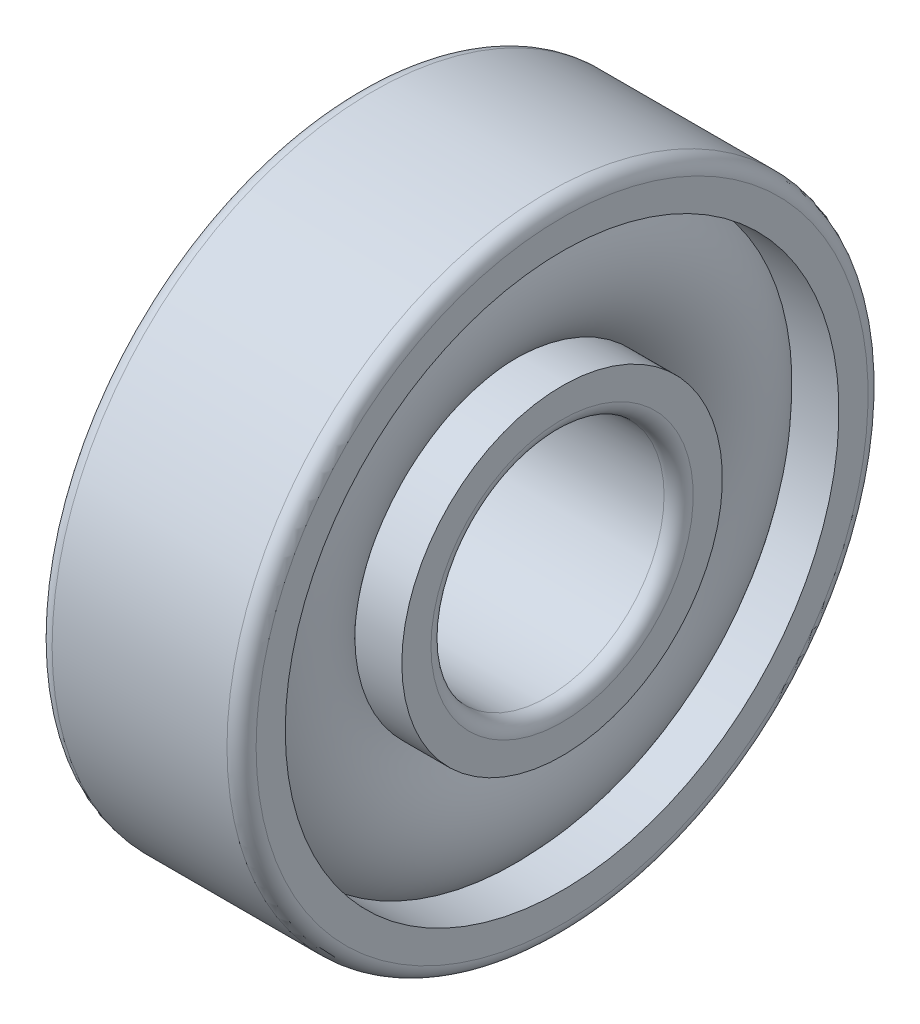
SolidWorks part; units mm, degrees
ref_plane "Plano frontal" through (0, 0, 0) normal (0, 0, 1) x (1, 0, 0)
ref_plane "Plano superior" through (0, 0, 0) normal (0, 1, 0) x (1, 0, 0)
ref_plane "Plano direito" through (0, 0, 0) normal (1, 0, 0) x (0, 0, -1)
sketch "Esboço1" plane through (0, 0, 0) normal (0, 0, 1) x (1, 0, 0)
  line L0 (0, 0) -> (29.7772, 0) construction
  line L1 (0, 0) -> (0, 7.5) construction
  line L2 (-3.5, 9.5) -> (3.5, 9.5)
  line L3 (-3.5, 4) -> (3.5, 4)
  line L4 (-3.5, 4) -> (-3.5, 11)
  line L5 (-3.5, 11) -> (3.5, 11)
  line L6 (3.5, 4) -> (3.5, 11)
  line L7 (-3.5, 4) -> (3.5, 11) construction
  line L8 (-3.5, 11) -> (3.5, 4) construction
  line L9 (0, 7.5) -> (4.1417, 7.5) construction
  line L10 (-3.5, 5.5) -> (3.5, 5.5)
  circle A0 centre (0, 7.5) radius 2.75
  dimension "D4" = 5.5
  dimension "D1" = 7
  dimension "D2" = 8
  dimension "D3" = 22
  dimension "D5" = 1.5
revolve "Revolução1" add sketch "Esboço1" angle 360 about L0
fillet "Filete1" radius 0.5 4 edges at (-3.5, 0, 4) (3.5, 0, 4) (-3.5, 0, 11) (3.5, 0, 11)
